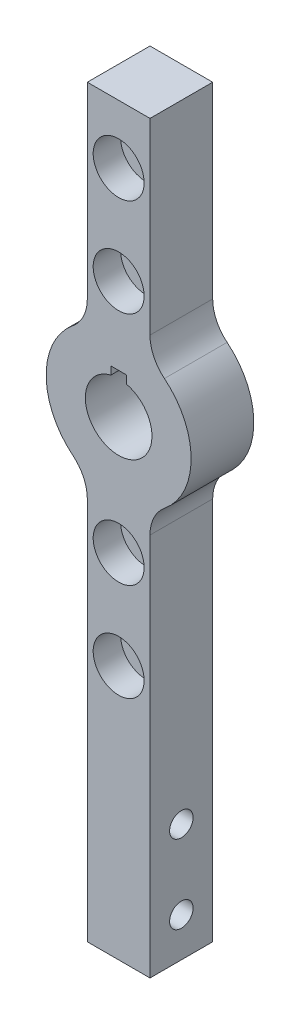
SolidWorks part; units mm, degrees
material "1060 Alloy"
ref_plane "Front Plane" through (0, 0, 0) normal (0, 0, 1) x (1, 0, 0)
ref_plane "Top Plane" through (0, 0, 0) normal (0, 1, 0) x (1, 0, 0)
ref_plane "Right Plane" through (0, 0, 0) normal (1, 0, 0) x (0, 0, -1)
sketch "Sketch1" plane through (0, 0, 0) normal (0, 0, 1) x (1, 0, 0)
  circle A0 centre (0, 0) radius 8.5
  circle A1 centre (0, 0) radius 18.5
  dimension "D1" = 17
  dimension "D2" = 37
extrude "Boss-Extrude1" add sketch "Sketch1" along normal mid plane 16
sketch "Sketch2" plane through (0, 0, 0) normal (0, 0, 1) x (1, 0, 0)
  line L0 (0, 0) -> (0, 40.1669) construction
  line L1 (-8, 70) -> (8, 70)
  line L2 (8, 70) -> (8, 16.6808)
  line L3 (8, 16.6808) -> (-8, 16.6808)
  line L4 (-8, 70) -> (-8, 16.6808)
  circle A0 centre (0, 0) radius 18.5 construction
  point P10 (0, 16.6808)
  point P11 (0, 70)
  dimension "D1" = 16
  dimension "D2" = 70
extrude "Boss-Extrude2" add sketch "Sketch2" along normal mid plane 16
sketch "Sketch3" plane through (0, 0, 0) normal (0, 0, 1) x (1, 0, 0)
  line L0 (0, 0) -> (0, -28.6568) construction
  line L1 (-8, -120) -> (8, -120)
  line L2 (8, -120) -> (8, -16.6808)
  line L3 (8, -16.6808) -> (-8, -16.6808)
  line L4 (-8, -120) -> (-8, -16.6808)
  arc A0 (-8, 16.6808) -> (8, 16.6808) centre (0, 0) ccw construction
  point P11 (0, -16.6808)
  point P12 (0, -120)
  dimension "D1" = 16
  dimension "D2" = 120
extrude "Boss-Extrude3" add sketch "Sketch3" along normal mid plane 16
sketch "Sketch4" plane through (0, 0, -8) normal (0, 0, -1) x (-1, 0, 0)
  line L0 (0, 0) -> (0, 36.1072) construction
  line L1 (2, 10.3) -> (-2, 10.3)
  line L2 (-2, 10.3) -> (-2, 8.2614)
  line L3 (-2, 8.2614) -> (2, 8.2614)
  line L4 (2, 10.3) -> (2, 8.2614)
  circle A0 centre (0, 0) radius 8.5 construction
  point P10 (0, 8.2614)
  point P11 (0, 10.3)
  dimension "D1" = 10.3
  dimension "D2" = 4
extrude "Cut-Extrude1" cut sketch "Sketch4" against normal through all
fillet "Fillet1" radius 10 4 edges at (8, -16.6808, 0) (-8, -16.6808, 0) (-8, 16.6808, 0) (8, 16.6808, 0)
sketch "Sketch7" plane through (0, 0, 8) normal (0, 0, 1) x (1, 0, 0)
  line L0 (0, -124.3895) -> (0, 76.2895) construction
  line L1 (8, 70) -> (-8, 70) construction
  circle A0 centre (0, 55) radius 6.5
  circle A1 centre (0, 30) radius 6.5
  dimension "D1" = 13
  dimension "D2" = 13
  dimension "D3" = 15
  dimension "D4" = 25
extrude "Cut-Extrude3" cut sketch "Sketch7" against normal blind 7
mirror "Mirror1" about plane through (0, 0, 0) normal (0, 1, 0) of "Cut-Extrude3"
sketch "Sketch8" plane through (0, 0, 1) normal (0, 0, 1) x (1, 0, 0)
  circle A0 centre (0, 55) radius 3
  circle A1 centre (0, 30) radius 3
  dimension "D1" = 6
  dimension "D2" = 6
extrude "Cut-Extrude4" cut sketch "Sketch8" against normal through all
mirror "Mirror2" about plane through (0, 0, 0) normal (0, 1, 0) of "Cut-Extrude4"
sketch "Sketch9" plane through (8, 0, 0) normal (1, 0, 0) x (0, 0, -1)
  line L0 (0, 0) -> (0, -128.2064) construction
  line L1 (-8, -120) -> (8, -120) construction
  circle A0 centre (0, -110) radius 3
  circle A1 centre (0, -90) radius 3
  dimension "D1" = 6
  dimension "D2" = 6
  dimension "D3" = 10
  dimension "D4" = 20
extrude "Cut-Extrude5" cut sketch "Sketch9" against normal through all
